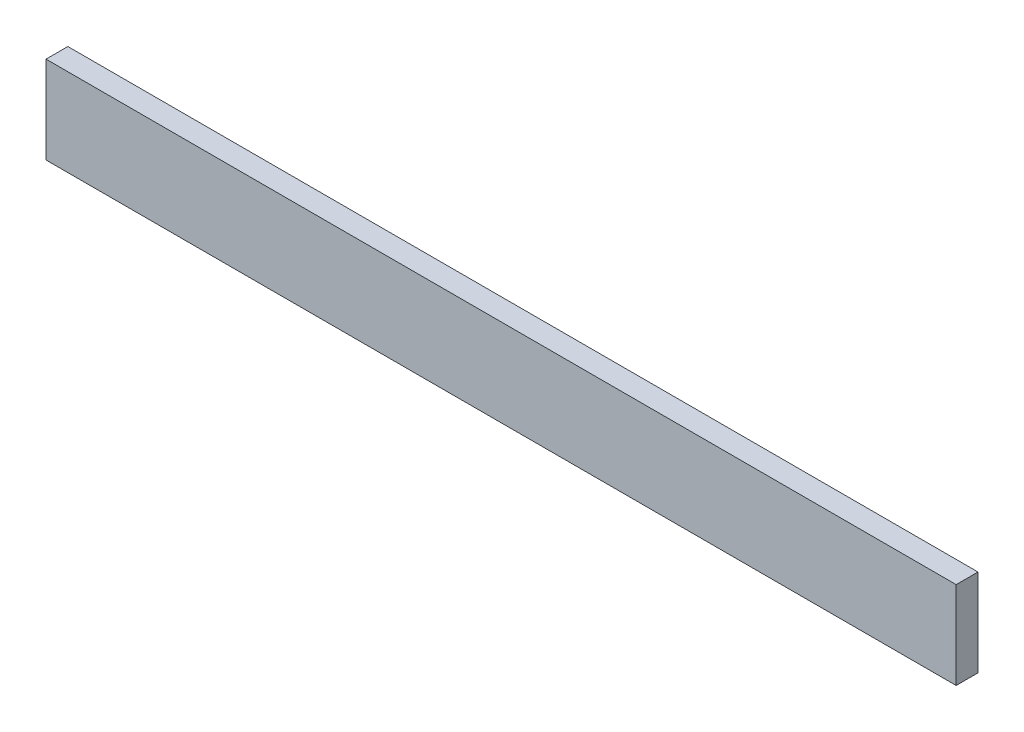
SolidWorks part; units mm, degrees
ref_plane "Front Plane" through (0, 0, 0) normal (0, 0, 1) x (1, 0, 0)
ref_plane "Top Plane" through (0, 0, 0) normal (0, 1, 0) x (1, 0, 0)
ref_plane "Right Plane" through (0, 0, 0) normal (1, 0, 0) x (0, 0, -1)
sketch "Sketch1" plane through (0, 0, 0) normal (0, 0, 1) x (1, 0, 0)
  line L0 (-83.7774, 0) -> (-95.7774, 0)
  line L1 (17.2226, 0) -> (29.2226, 0)
  line L2 (-83.7774, 0) -> (17.2226, 0)
  line L3 (-95.7774, 0) -> (-95.7774, -12)
  line L4 (-95.7774, -12) -> (29.2226, -12)
  line L5 (29.2226, -12) -> (29.2226, 0)
  point P6 (0, 0)
  dimension "D1" = 101
  dimension "D2" = 125
  dimension "D3" = 12
  dimension "D4" = 12
  dimension "D5" = 12
extrude "Boss-Extrude1" add sketch "Sketch1" along normal blind 3
